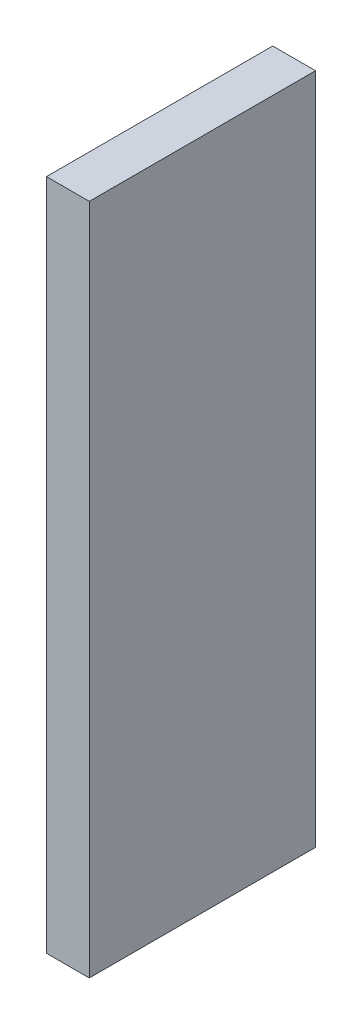
SolidWorks part; units mm, degrees
ref_plane "Front Plane" through (0, 0, 0) normal (0, 0, 1) x (1, 0, 0)
ref_plane "Top Plane" through (0, 0, 0) normal (0, 1, 0) x (1, 0, 0)
ref_plane "Right Plane" through (0, 0, 0) normal (1, 0, 0) x (0, 0, -1)
sketch "Sketch1" plane through (0, 0, 0) normal (0, 0, 1) x (1, 0, 0)
  line L0 (0, 0) -> (0, 44)
  line L1 (0, 44) -> (2.8, 44)
  line L2 (2.8, 44) -> (2.8, 0)
  line L3 (2.8, 0) -> (0, 0)
extrude "Boss-Extrude1" add sketch "Sketch1" along normal blind 14.8
